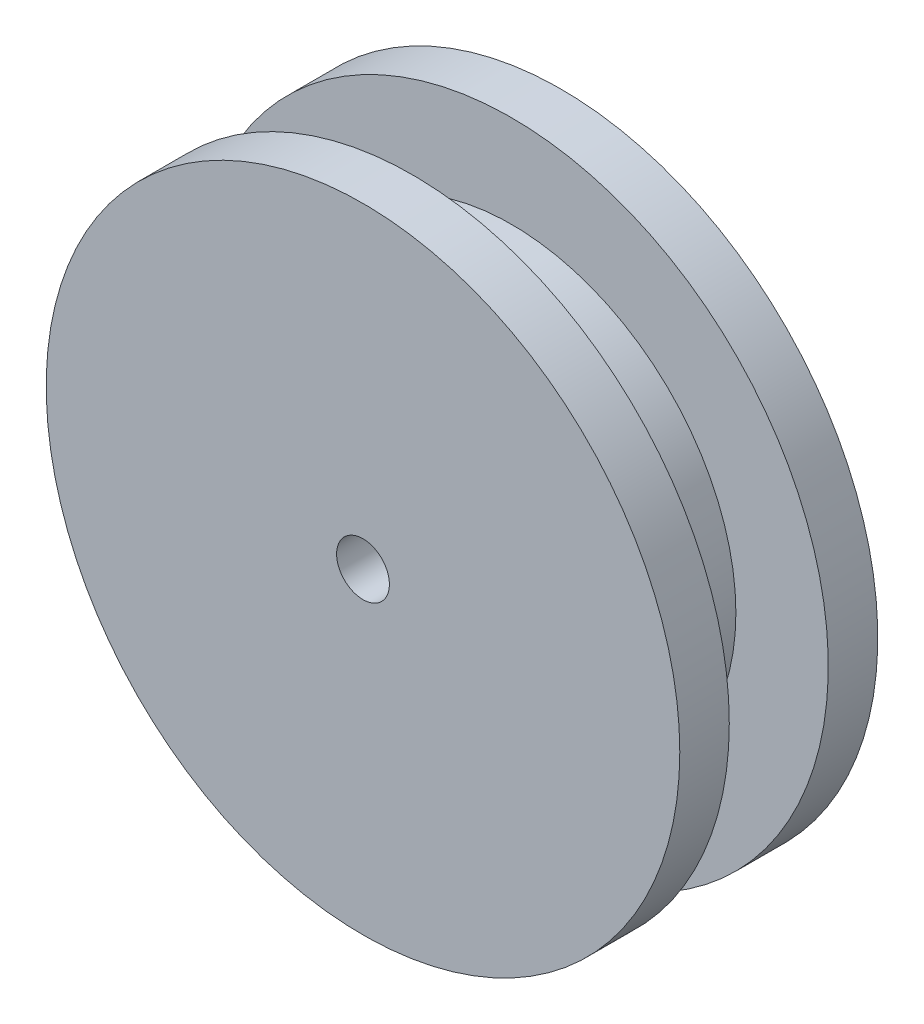
SolidWorks part; units mm, degrees
ref_plane "Front Plane" through (0, 0, 0) normal (0, 0, 1) x (1, 0, 0)
ref_plane "Top Plane" through (0, 0, 0) normal (0, 1, 0) x (1, 0, 0)
ref_plane "Right Plane" through (0, 0, 0) normal (1, 0, 0) x (0, 0, -1)
sketch "Sketch1" plane through (0, 0, 0) normal (0, 0, 1) x (1, 0, 0)
  circle A0 centre (0, 0) radius 34
  dimension "D1" = 68
extrude "Boss-Extrude1" add sketch "Sketch1" along normal blind 15
sketch "Sketch2" plane through (0, 0, 15) normal (0, 0, 1) x (1, 0, 0)
  circle A0 centre (0, 0) radius 48
  dimension "D1" = 96
extrude "Boss-Extrude2" add sketch "Sketch2" along normal blind 7.5
sketch "Sketch3" plane through (0, 0, 0) normal (0, 0, -1) x (-1, 0, 0)
  circle A0 centre (0, 0) radius 48
extrude "Boss-Extrude3" add sketch "Sketch3" along normal blind 7.5
sketch "Sketch4" plane through (0, 0, -7.5) normal (0, 0, -1) x (-1, 0, 0)
  circle A0 centre (0, 0) radius 4
extrude "Cut-Extrude1" cut sketch "Sketch4" against normal blind 30
